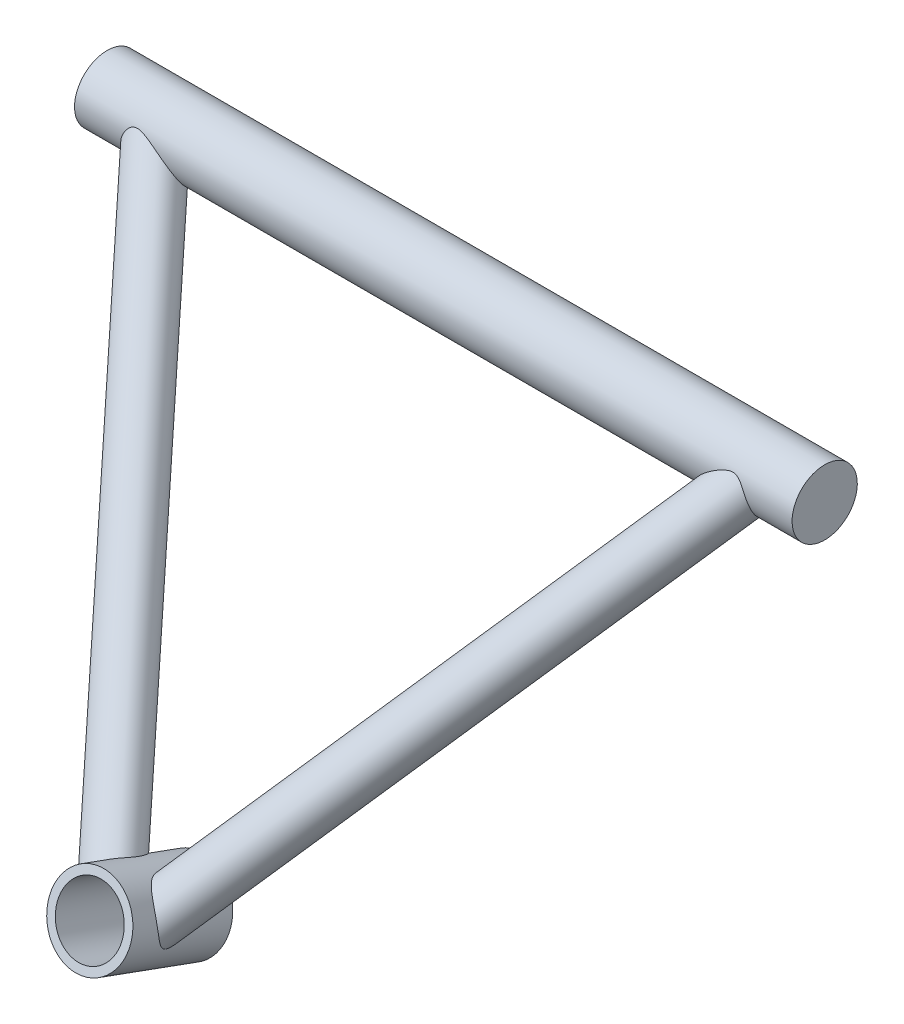
SolidWorks part; units mm, degrees
material "AISI 4130 Steel, normalized at 870C"
ref_plane "Front Plane" through (0, 0, 0) normal (0, 0, 1) x (1, 0, 0)
ref_plane "Top Plane" through (0, 0, 0) normal (0, 1, 0) x (1, 0, 0)
ref_plane "Right Plane" through (0, 0, 0) normal (1, 0, 0) x (0, 0, -1)
sketch "Sketch3" plane through (0, 0, 0) normal (0, 1, 0) x (1, 0, 0)
  line L0 (-5.08, -6.35) -> (5.08, -6.35) construction
  line L2 (0, -88.2205) -> (0, 88.2205) construction
  line L3 (5.08, 0) -> (-5.08, 0) construction
  dimension "D1" = 5.08
  dimension "D2" = 10.16
  dimension "D3" = 6.35
  dimension "D4" = 10.16
  dimension "D5" = 5.08
ref_plane "Plane1" through (0, 3.1576, 3.5069) normal (0, 0.6691, 0.7431) x (1, 0, 0)
ref_plane "Plane3" through (0, 0, 0) normal (0, 0.342, 0.9397) x (-1, 0, 0)
sketch "Sketch1" plane through (0, 0, 0) normal (0, 0.342, 0.9397) x (1, 0, 0)
  circle A0 centre (0, 0) radius 15.875
  dimension "D1" = 31.75
extrude "Boss-Extrude1" add sketch "Sketch1" along normal mid plane 41.402 contours A0
sketch "Sketch4" plane through (0, 3.1576, 3.5069) normal (0, 0.6691, 0.7431) x (1, 0, 0)
  line L0 (-5.08, -4.249) -> (-119.38, 193.7244)
  line L2 (0, -99.4638) -> (0, 99.4638) construction
  dimension "D2" = 30
  dimension "D3" = 228.6
sweep "Sweep1" add path "Sketch4" circular profile diameter 19.05 parameters "D3"=19.05
sketch "Sketch15" plane through (0, 3.1576, 3.5069) normal (0, 0.6691, 0.7431) x (1, 0, 0)
  line L0 (5.08, -4.249) -> (119.38, 193.7244)
  line L1 (0, -99.4638) -> (0, 99.4638) construction
  dimension "D1" = 228.6
  dimension "D2" = 30
sweep "Sweep2" add path "Sketch15" circular profile diameter 19.05 parameters "D3"=19.05
sketch "Sketch36" plane through (-113.7301, 146.3894, -131.8096) normal (-0.5, 0.6436, -0.5795) x (0.8659, 0.3845, -0.3201)
  circle A0 centre (-6.4312, -4.8446) radius 7.9375
  dimension "D1" = 15.875
extrude "Cut-Extrude2" cut sketch "Sketch36" against normal up to surface (248.4296 mm away)
sketch "Sketch37" plane through (113.7301, 146.3894, -131.8096) normal (0.5, 0.6436, -0.5795) x (0.8659, -0.3845, 0.3201)
  circle A0 centre (6.4312, -4.8446) radius 7.9375
  dimension "D1" = 15.875
extrude "Cut-Extrude3" cut sketch "Sketch37" against normal up to surface (215.8867 mm away)
sketch "Sketch77" plane through (0, 7.0802, 19.4526) normal (0, 0.342, 0.9397) x (1, 0, 0)
  circle A1 centre (0, 0) radius 15.875
extrude "Boss-Extrude2" add sketch "Sketch77" against normal up to surface (41.402 mm away) up to face at (0, -21.9978, -14.023)
sketch "Sketch2" plane through (0, -7.0802, -19.4526) normal (0, -0.342, -0.9397) x (-1, 0, 0)
  circle A0 centre (0, 0) radius 12.7
  dimension "D1" = 25.4
extrude "Cut-Extrude1" cut sketch "Sketch2" against normal up to next
ref_plane "Plane2" through (0, 0, -127) normal (0, 0, 1) x (1, 0, 0)
ref_plane "Plane4" through (0, 177.8, 0) normal (0, 1, 0) x (1, 0, 0)
sketch "Sketch40" plane through (-106.934, 0, -127) normal (0, 0, 1) x (1, 0, 0)
  line L0 (108.4431, 144.78) -> (50108.4431, 144.78) construction
  line L1 (-32.766, 144.78) -> (246.634, 144.78)
  point P0 (106.934, 144.78)
  point P1 (106.934, 144.78)
  dimension "D1" = 279.4
  dimension "D5" = 144.78
sweep "Sweep5" add path "Sketch40" circular profile diameter 25.4 parameters "D3"=25.4
